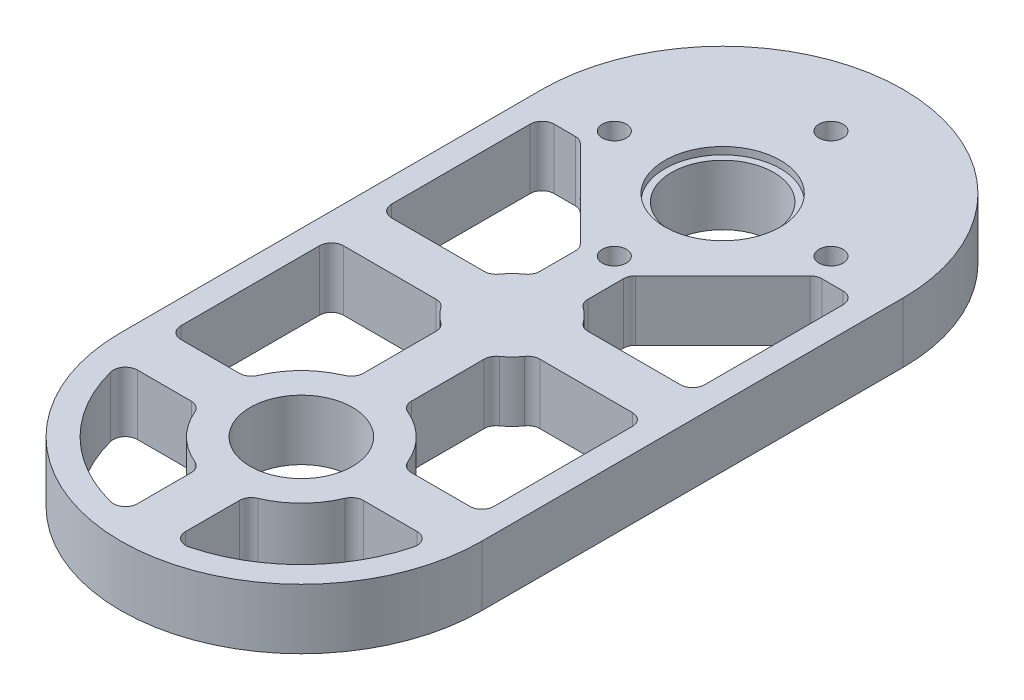
SolidWorks part; units mm, degrees
ref_plane "前视基准面" through (0, 0, 0) normal (0, 0, 1) x (1, 0, 0)
ref_plane "上视基准面" through (0, 0, 0) normal (0, 1, 0) x (1, 0, 0)
ref_plane "右视基准面" through (0, 0, 0) normal (1, 0, 0) x (0, 0, -1)
other "Configuration Table"
sketch "草图1" plane through (0, 0, 0) normal (0, 1, 0) x (1, 0, 0)
  line L0 (30, 0) -> (30, -70)
  line L1 (-30, 0) -> (-30, -70)
  arc A0 (30, 0) -> (-30, 0) centre (0, 0) ccw
  arc A1 (-30, -70) -> (30, -70) centre (0, -70) ccw
  circle A2 centre (0, 0) radius 4
  circle A3 centre (0, 18) radius 2
  circle A4 centre (18, 0) radius 2
  circle A5 centre (0, -18) radius 2
  circle A6 centre (-18, 0) radius 2
  point P19 (0, 0)
  dimension "D1" = 60
  dimension "D2" = 8
  dimension "D3" = 4
  dimension "D4" = 18
  dimension "D7" = 30
  dimension "D6" = 70
  dimension "D5" = 4
extrude "凸台-拉伸1" add sketch "草图1" along normal blind 10
sketch "草图2" plane through (0, 10, 0) normal (0, 1, 0) x (1, 0, 0)
  circle A0 centre (0, -70) radius 8.5
  dimension "D1" = 17
extrude "切除-拉伸1" cut sketch "草图2" against normal blind 10
sketch "草图3" plane through (0, 0, 0) normal (0, -1, 0) x (-1, 0, 0)
  line L0 (0, -70) -> (-5, -70) construction
  line L1 (-5, -70) -> (-5, -45) construction
  line L2 (-14.5, -45) -> (-18, -45) construction
  line L3 (-18, -42) -> (-5, -42)
  line L4 (-18, -48) -> (-5, -48)
  arc A0 (-5, -48) -> (-5, -42) centre (-5, -45) ccw
  arc A1 (-18, -42) -> (-18, -48) centre (-18, -45) ccw
  dimension "D4" = 6
  dimension "D5" = 6
  dimension "D1" = 5
  dimension "D2" = 25
  dimension "D3" = 13
sketch "草图4" plane through (0, 0, 0) normal (0, -1, 0) x (1, 0, 0)
  line L0 (0, 70) -> (0, 35) construction
  circle A0 centre (0, 35) radius 2.5
  dimension "D1" = 5
extrude "切除-拉伸3" cut sketch "草图4" against normal blind 30
sketch "草图5" plane through (0, 0, 0) normal (0, -1, 0) x (-1, 0, 0)
  circle A0 centre (0, -35) radius 5.5
  dimension "D1" = 11
sketch "草图9" plane through (0, 0, 0) normal (0, -1, 0) x (-1, 0, 0)
  line L0 (0, -18) -> (18, 0) construction
  line L1 (0, -18) -> (-18, 0) construction
  line L2 (0, -18) -> (0, -35) construction
  line L3 (0, -35) -> (30, -35) construction
  line L4 (30, 0) -> (30, -70) construction
  line L5 (30, -35) -> (30, 0) construction
  line L6 (30, 0) -> (18, 0) construction
  line L7 (0, -35) -> (-30, -35) construction
  line L8 (-30, -70) -> (-30, 0) construction
  line L9 (-30, -35) -> (-30, 0) construction
  line L10 (-30, 0) -> (-18, 0) construction
  line L11 (0, -70) -> (0, -35) construction
  line L12 (7.0282, -70) -> (30, -70) construction
  line L13 (0, -70) -> (-30, -70) construction
  line L14 (0, -70) -> (0, -100) construction
  line L15 (7.5, -31) -> (26, -31)
  line L16 (26, -31) -> (26, -4)
  line L17 (26, -4) -> (19.6569, -4)
  line L18 (4, -19.6569) -> (19.6569, -4)
  line L19 (4, -19.6569) -> (4, -27.5)
  line L20 (30, -70) -> (30, -35) construction
  line L21 (12.8938, -66) -> (26, -66)
  line L22 (26, -66) -> (26, -39)
  line L23 (7.5, -39) -> (26, -39)
  line L24 (4, -57.1062) -> (4, -42.5)
  line L25 (12.8938, -74) -> (25.6905, -74)
  line L26 (4, -82.8938) -> (4, -95.6905)
  line L27 (4, -74) -> (4, -100) construction
  line L28 (4, -74) -> (30, -74) construction
  line L29 (0, -70) -> (30, -70) construction
  line L30 (4, -66) -> (26, -66) construction
  line L31 (4, -66) -> (4, -39) construction
  line L32 (4, -39) -> (26, -39) construction
  line L33 (4, -31) -> (26, -31) construction
  line L34 (4, -19.6569) -> (4, -31) construction
  arc A2 (7.5, -31) -> (4, -27.5) centre (0, -35) ccw
  arc A3 (12.8938, -66) -> (4, -57.1062) centre (0, -70) ccw
  arc A5 (4, -95.6905) -> (25.6905, -74) centre (0, -70) ccw
  arc A6 (4, -82.8938) -> (12.8938, -74) centre (0, -70) ccw
  arc A8 (4, -42.5) -> (7.5, -39) centre (0, -35) ccw
  dimension "D2" = 17
  dimension "D3" = 27
  dimension "D1" = 4
  dimension "D4" = 4
  dimension "D5" = 4
extrude "切除-拉伸8" cut sketch "草图9" against normal blind 10
ref_plane "基准面2" through (0, 0, 0) normal (-1, 0, 0) x (0, 0, 1)
fillet "圆角1" radius 2 16 edges at (-26, 5, 4) (-19.6569, 5, 4) (-4, 5, 19.6569) (-4, 5, 27.5) (-7.5, 5, 31) (-26, 5, 31) (-26, 5, 39) (-26, 5, 66) (-7.5, 5, 39) (-4, 5, 42.5) (-4, 5, 57.1062) (-12.8938, 5, 66) (-12.8938, 5, 74) (-4, 5, 82.8938) (-4, 5, 95.6905) (-25.6905, 5, 74)
mirror "镜向1" about plane through (0, 0, 0) normal (-1, 0, 0) of "圆角1", "切除-拉伸8"
sketch "草图10" plane through (0, 0, 0) normal (0, -1, 0) x (-1, 0, 0)
  line L0 (0, 0) -> (0, 18) construction
  circle A0 centre (0, 9) radius 1.05
  dimension "D1" = 2.1
sketch "草图11" plane through (0, 0, 0) normal (0, -1, 0) x (-1, 0, 0)
  circle A0 centre (0, -35) radius 2.5
extrude "凸台-拉伸2" add sketch "草图11" against normal up to surface (10 mm away) up to face at (-14.4174, 10, 19.4755)
sketch "草图12" plane through (0, 0, 0) normal (0, -1, 0) x (-1, 0, 0)
  circle A0 centre (0, 0) radius 8.5
  dimension "D1" = 17
extrude "切除-拉伸10" cut sketch "草图12" against normal blind 21
sketch "草图13" plane through (0, 10, 0) normal (0, 1, 0) x (1, 0, 0)
  circle A0 centre (0, 0) radius 9.6
  dimension "D1" = 19.2
extrude "切除-拉伸11" cut sketch "草图13" against normal blind 1.2
sketch "草图14" plane through (0, 0, 0) normal (0, -1, 0) x (-1, 0, 0)
  circle A0 centre (0, 0) radius 8.5
  circle A1 centre (0, 0) radius 12
  dimension "D1" = 24
extrude "凸台-拉伸3" add sketch "草图14" along normal blind 1.2
